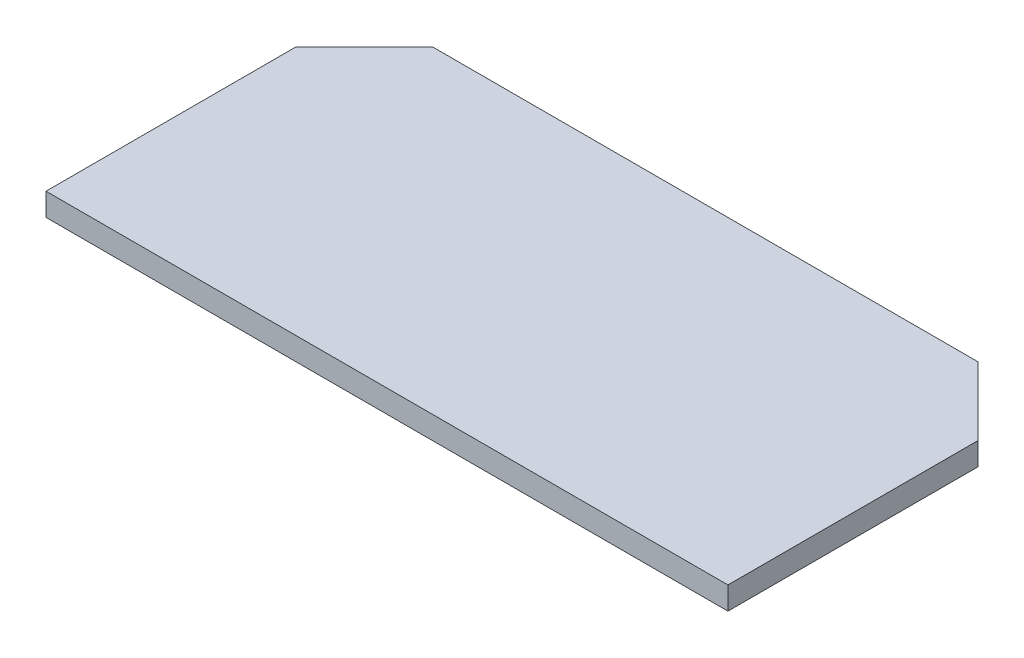
SolidWorks part; units mm, degrees
ref_plane "front" through (0, 0, 0) normal (0, 0, 1) x (1, 0, 0)
ref_plane "top" through (0, 0, 0) normal (0, 1, 0) x (1, 0, 0)
ref_plane "right" through (0, 0, 0) normal (1, 0, 0) x (0, 0, -1)
sketch "Sketch1" plane through (0, 0, 0) normal (1, 0, 0) x (0, 0, -1)
  line L0 (-57.2164, 139.7) -> (-57.2164, 460.3722) construction
  line L1 (1.2678, 498.8052) -> (-40.3314, 504.8368) construction
  line L2 (-50.8, 139.7) -> (53.3356, 857.9104)
  line L3 (46.9856, 921.4104) -> (46.9856, 870.6104)
  line L4 (-57.2164, 139.7) -> (-50.8, 139.7)
  line L5 (40.6356, 934.1104) -> (-10.1644, 934.1104)
  line L6 (12.853, 622.9604) -> (-76.047, 622.9604)
  line L7 (-76.047, 622.9604) -> (-76.047, 616.6104)
  line L8 (-22.8644, 921.4104) -> (-22.8644, 857.9104)
  line L9 (-137.6884, 660.4) -> (-130.3433, 660.4)
  line L10 (-16.5144, 921.4104) -> (-16.5144, 870.6104)
  line L11 (-10.1644, 927.7604) -> (40.6356, 927.7604)
  line L12 (-76.047, 616.6104) -> (11.9323, 616.6104)
  line L13 (25.7429, 711.8604) -> (-62.2364, 711.8604)
  line L14 (-62.2364, 711.8604) -> (-62.2364, 718.2104)
  line L15 (-62.2364, 718.2104) -> (26.6636, 718.2104)
  line L16 (40.6356, 864.2604) -> (-10.1644, 864.2604)
  line L17 (-137.6884, 660.4) -> (-22.8644, 857.9104)
  line L18 (-15.5193, 857.9104) -> (46.9192, 857.9104)
  line L19 (46.9192, 857.9104) -> (26.6636, 718.2104)
  line L20 (25.7429, 711.8604) -> (12.853, 622.9604)
  line L21 (11.9323, 616.6104) -> (-57.2164, 139.7)
  line L22 (53.3356, 857.9104) -> (53.3356, 921.4104)
  line L23 (-15.5193, 857.9104) -> (-130.3433, 660.4)
  arc A0 (-10.1644, 934.1104) -> (-22.8644, 921.4104) centre (-10.1644, 921.4104) ccw
  arc A1 (40.6356, 934.1104) -> (53.3356, 921.4104) centre (40.6356, 921.4104) cw
  arc A2 (46.9856, 870.6104) -> (40.6356, 864.2604) centre (40.6356, 870.6104) cw
  arc A3 (40.6356, 927.7604) -> (46.9856, 921.4104) centre (40.6356, 921.4104) cw
  arc A4 (-10.1644, 927.7604) -> (-16.5144, 921.4104) centre (-10.1644, 921.4104) ccw
  arc A5 (-10.1644, 864.2604) -> (-16.5144, 870.6104) centre (-10.1644, 870.6104) cw
  dimension "D13" = 12.7
  dimension "D14" = 6.35
  dimension "D1" = 6.35
  dimension "D2" = 160.7058
  dimension "D3" = 6.35
  dimension "D4" = 6.35
  dimension "D5" = 6.35
  dimension "D6" = 88.9
  dimension "D7" = 88.9
  dimension "D8" = 101.6
  dimension "D9" = 215.9
  dimension "D10" = 6.35
  dimension "D11" = 6.35
  dimension "D12" = 6.35
  dimension "D15" = 6.35
  dimension "D16" = 273.7104
  dimension "D17" = 520.7
  dimension "D18" = 184.6075
  dimension "D19" = 76.2
  dimension "D20" = 76.2
  dimension "D21" = 8.25
  dimension "D22" = 139.7
  dimension "D23" = 50.8
sketch "Sketch2" plane through (0, 0, 0) normal (0, 1, 0) x (1, 0, 0)
  line L0 (-95.25, -19.05) -> (-76.2, 0)
  line L1 (-76.2, 0) -> (76.2, 0)
  line L2 (-95.25, -19.05) -> (-95.25, -88.9)
  line L3 (-95.25, -88.9) -> (95.25, -88.9)
  line L4 (95.25, -19.05) -> (95.25, -88.9)
  line L5 (76.2, 0) -> (95.25, -19.05)
  line L6 (0, 0) -> (0, -49.53) construction
  dimension "D1" = 19.05
  dimension "D2" = 190.5
  dimension "D3" = 88.9
  dimension "D4" = 19.05
extrude "Base-Extrude" add sketch "Sketch2" against normal blind 6.35
